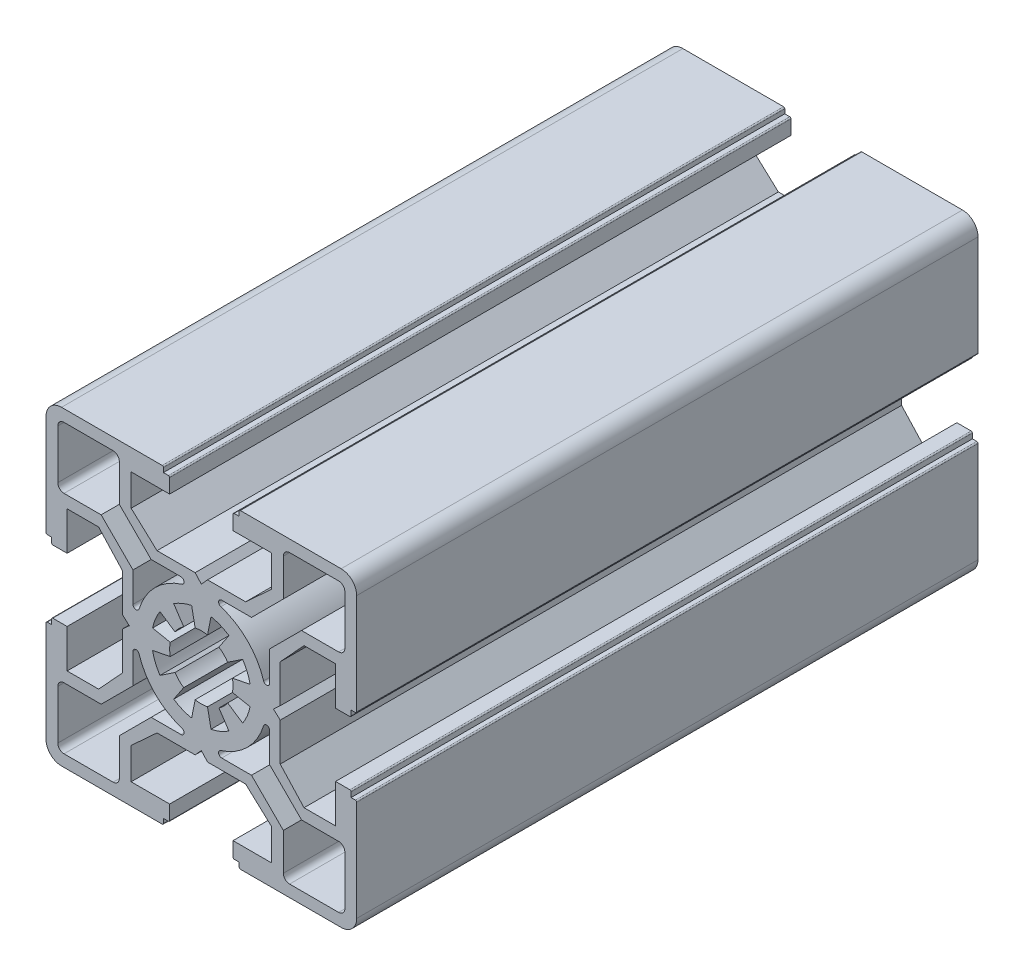
SolidWorks part; units mm, degrees
ref_plane "前视基准面" through (0, 0, 0) normal (0, 0, 1) x (1, 0, 0)
ref_plane "上视基准面" through (0, 0, 0) normal (0, 1, 0) x (1, 0, 0)
ref_plane "右视基准面" through (0, 0, 0) normal (1, 0, 0) x (0, 0, -1)
sketch "草图1" plane through (0, 0, 0) normal (0, 0, 1) x (1, 0, 0)
  line B0 (-6.3, 25) -> (-22.5, 25)
  line B1 (-25, 22.5) -> (-25, 6.3)
  line B2 (22.5, 25) -> (6.3, 25)
  line B3 (-25, -6.3) -> (-25, -22.5)
  line B4 (25, 6.3) -> (25, 22.5)
  line B5 (-22.5, -25) -> (-6.3, -25)
  line B6 (-6.1, -24.8) -> (-6.1, -24.1)
  line B7 (-6.1, -24.1) -> (-5.3, -24.1)
  line B8 (-5.1, -23.9) -> (-5.1, -21.6)
  line B9 (-5.1, -21.6) -> (-11.3, -21.6)
  line B10 (-11.3, -21.6) -> (-11.3, -16.53)
  line B11 (-11.3, -16.53) -> (-7.1302, -12.7)
  line B12 (-7.1302, -12.7) -> (-1, -12.7)
  line B13 (-1, -12.7) -> (0, -11.6)
  line B14 (0, -11.6) -> (1, -12.7)
  line B15 (1, -12.7) -> (7.1302, -12.7)
  line B16 (7.1302, -12.7) -> (11.3, -16.53)
  line B17 (11.3, -16.53) -> (11.3, -21.6)
  line B18 (11.3, -21.6) -> (5.1, -21.6)
  line B19 (5.1, -21.6) -> (5.1, -23.9)
  line B20 (5.3, -24.1) -> (6.1, -24.1)
  line B21 (6.1, -24.1) -> (6.1, -24.8)
  line B22 (25, -22.5) -> (25, -6.3)
  line B23 (6.3, -25) -> (22.5, -25)
  line B24 (2.8334, 4.2405) -> (4.4446, 6.6518)
  line B25 (1.5607, 7.8463) -> (0.995, 5.002)
  line B26 (-0.995, 5.002) -> (-1.5607, 7.8463)
  line B27 (-4.4446, 6.6518) -> (-2.8334, 4.2405)
  line B28 (-4.2405, 2.8334) -> (-6.6518, 4.4446)
  line B29 (-7.8463, 1.5607) -> (-5.002, 0.995)
  line B30 (-5.002, -0.995) -> (-7.8463, -1.5607)
  line B31 (-6.6518, -4.4446) -> (-4.2405, -2.8334)
  line B32 (-2.8334, -4.2405) -> (-4.4446, -6.6518)
  line B33 (-1.5607, -7.8463) -> (-0.995, -5.002)
  line B34 (0.995, -5.002) -> (1.5607, -7.8463)
  line B35 (4.4446, -6.6518) -> (2.8334, -4.2405)
  line B36 (4.2405, -2.8334) -> (6.6518, -4.4446)
  line B37 (7.8463, -1.5607) -> (5.002, -0.995)
  line B38 (5.002, 0.995) -> (7.8463, 1.5607)
  line B39 (6.6518, 4.4446) -> (4.2405, 2.8334)
  line B40 (3.2787, -11) -> (8.0757, -11)
  line B41 (8.0757, -11) -> (13.2, -16.1243)
  line B42 (13.2, -16.1243) -> (13.2, -22.1)
  line B43 (14.2, -23.1) -> (22.1, -23.1)
  line B44 (23.1, -22.1) -> (23.1, -14.2)
  line B45 (22.1, -13.2) -> (16.1243, -13.2)
  line B46 (16.1243, -13.2) -> (11, -8.0757)
  line B47 (11, -8.0757) -> (11, -3.2787)
  line B48 (-8.0757, 11) -> (-13.2, 16.1243)
  line B49 (-13.2, 16.1243) -> (-13.2, 22.1)
  line B50 (-14.2, 23.1) -> (-22.1, 23.1)
  line B51 (-23.1, 22.1) -> (-23.1, 14.2)
  line B52 (-22.1, 13.2) -> (-16.1243, 13.2)
  line B53 (-16.1243, 13.2) -> (-11, 8.0757)
  line B54 (-11, 8.0757) -> (-11, 3.2787)
  line B55 (-3.2787, 11) -> (-8.0757, 11)
  line B56 (13.2, 22.1) -> (13.2, 16.1243)
  line B57 (13.2, 16.1243) -> (8.0757, 11)
  line B58 (8.0757, 11) -> (3.2787, 11)
  line B59 (11, 3.2787) -> (11, 8.0757)
  line B60 (11, 8.0757) -> (16.1243, 13.2)
  line B61 (16.1243, 13.2) -> (22.1, 13.2)
  line B62 (23.1, 14.2) -> (23.1, 22.1)
  line B63 (22.1, 23.1) -> (14.2, 23.1)
  line B64 (-16.1243, -13.2) -> (-22.1, -13.2)
  line B65 (-23.1, -14.2) -> (-23.1, -22.1)
  line B66 (-22.1, -23.1) -> (-14.2, -23.1)
  line B67 (-13.2, -22.1) -> (-13.2, -16.1243)
  line B68 (-13.2, -16.1243) -> (-8.0757, -11)
  line B69 (-8.0757, -11) -> (-3.2787, -11)
  line B70 (-11, -3.2787) -> (-11, -8.0757)
  line B71 (-11, -8.0757) -> (-16.1243, -13.2)
  line B72 (24.8, -6.1) -> (24.1, -6.1)
  line B73 (24.1, -6.1) -> (24.1, -5.3)
  line B74 (23.9, -5.1) -> (21.6, -5.1)
  line B75 (21.6, -5.1) -> (21.6, -11.3)
  line B76 (21.6, -11.3) -> (16.53, -11.3)
  line B77 (16.53, -11.3) -> (12.7, -7.1302)
  line B78 (12.7, -7.1302) -> (12.7, -1)
  line B79 (12.7, -1) -> (11.6, 0)
  line B80 (11.6, 0) -> (12.7, 1)
  line B81 (12.7, 1) -> (12.7, 7.1302)
  line B82 (12.7, 7.1302) -> (16.53, 11.3)
  line B83 (16.53, 11.3) -> (21.6, 11.3)
  line B84 (21.6, 11.3) -> (21.6, 5.1)
  line B85 (21.6, 5.1) -> (23.9, 5.1)
  line B86 (24.1, 5.3) -> (24.1, 6.1)
  line B87 (24.1, 6.1) -> (24.8, 6.1)
  line B88 (6.1, 24.8) -> (6.1, 24.1)
  line B89 (6.1, 24.1) -> (5.3, 24.1)
  line B90 (5.1, 23.9) -> (5.1, 21.6)
  line B91 (5.1, 21.6) -> (11.3, 21.6)
  line B92 (11.3, 21.6) -> (11.3, 16.53)
  line B93 (11.3, 16.53) -> (7.1302, 12.7)
  line B94 (7.1302, 12.7) -> (1, 12.7)
  line B95 (1, 12.7) -> (0, 11.6)
  line B96 (0, 11.6) -> (-1, 12.7)
  line B97 (-1, 12.7) -> (-7.1302, 12.7)
  line B98 (-7.1302, 12.7) -> (-11.3, 16.53)
  line B99 (-11.3, 16.53) -> (-11.3, 21.6)
  line B100 (-11.3, 21.6) -> (-5.1, 21.6)
  line B101 (-5.1, 21.6) -> (-5.1, 23.9)
  line B102 (-5.3, 24.1) -> (-6.1, 24.1)
  line B103 (-6.1, 24.1) -> (-6.1, 24.8)
  line B104 (-24.8, 6.1) -> (-24.1, 6.1)
  line B105 (-24.1, 6.1) -> (-24.1, 5.3)
  line B106 (-23.9, 5.1) -> (-21.6, 5.1)
  line B107 (-21.6, 5.1) -> (-21.6, 11.3)
  line B108 (-21.6, 11.3) -> (-16.53, 11.3)
  line B109 (-16.53, 11.3) -> (-12.7, 7.1302)
  line B110 (-12.7, 7.1302) -> (-12.7, 1)
  line B111 (-12.7, 1) -> (-11.6, 0)
  line B112 (-11.6, 0) -> (-12.7, -1)
  line B113 (-12.7, -1) -> (-12.7, -7.1302)
  line B114 (-12.7, -7.1302) -> (-16.53, -11.3)
  line B115 (-16.53, -11.3) -> (-21.6, -11.3)
  line B116 (-21.6, -11.3) -> (-21.6, -5.1)
  line B117 (-21.6, -5.1) -> (-23.9, -5.1)
  line B118 (-24.1, -5.3) -> (-24.1, -6.1)
  line B119 (-24.1, -6.1) -> (-24.8, -6.1)
  arc B120 (-22.5, 25) -> (-25, 22.5) centre (-22.5, 22.5) ccw
  arc B121 (25, 22.5) -> (22.5, 25) centre (22.5, 22.5) ccw
  arc B122 (-25, -22.5) -> (-22.5, -25) centre (-22.5, -22.5) ccw
  arc B123 (-6.3, -25) -> (-6.1, -24.8) centre (-6.3, -24.8) ccw
  arc B124 (-5.3, -24.1) -> (-5.1, -23.9) centre (-5.3, -23.9) ccw
  arc B125 (5.1, -23.9) -> (5.3, -24.1) centre (5.3, -23.9) ccw
  arc B126 (6.1, -24.8) -> (6.3, -25) centre (6.3, -24.8) ccw
  arc B127 (22.5, -25) -> (25, -22.5) centre (22.5, -22.5) ccw
  arc B128 (4.2405, 2.8334) -> (2.8334, 4.2405) centre (0, 0) ccw
  arc B129 (4.4446, 6.6518) -> (1.5607, 7.8463) centre (0, 0) ccw
  arc B130 (0.995, 5.002) -> (-0.995, 5.002) centre (0, 0) ccw
  arc B131 (-1.5607, 7.8463) -> (-4.4446, 6.6518) centre (0, 0) ccw
  arc B132 (-2.8334, 4.2405) -> (-4.2405, 2.8334) centre (0, 0) ccw
  arc B133 (-6.6518, 4.4446) -> (-7.8463, 1.5607) centre (0, 0) ccw
  arc B134 (-5.002, 0.995) -> (-5.002, -0.995) centre (0, 0) ccw
  arc B135 (-7.8463, -1.5607) -> (-6.6518, -4.4446) centre (0, 0) ccw
  arc B136 (-4.2405, -2.8334) -> (-2.8334, -4.2405) centre (0, 0) ccw
  arc B137 (-4.4446, -6.6518) -> (-1.5607, -7.8463) centre (0, 0) ccw
  arc B138 (-0.995, -5.002) -> (0.995, -5.002) centre (0, 0) ccw
  arc B139 (1.5607, -7.8463) -> (4.4446, -6.6518) centre (0, 0) ccw
  arc B140 (2.8334, -4.2405) -> (4.2405, -2.8334) centre (0, 0) ccw
  arc B141 (6.6518, -4.4446) -> (7.8463, -1.5607) centre (0, 0) ccw
  arc B142 (5.002, -0.995) -> (5.002, 0.995) centre (0, 0) ccw
  arc B143 (7.8463, 1.5607) -> (6.6518, 4.4446) centre (0, 0) ccw
  arc B144 (3.1297, -10.0227) -> (10.0227, -3.1297) centre (0, 0) ccw
  arc B145 (3.1297, -10.0227) -> (3.2787, -11) centre (3.2787, -10.5) ccw
  arc B146 (13.2, -22.1) -> (14.2, -23.1) centre (14.2, -22.1) ccw
  arc B147 (22.1, -23.1) -> (23.1, -22.1) centre (22.1, -22.1) ccw
  arc B148 (23.1, -14.2) -> (22.1, -13.2) centre (22.1, -14.2) ccw
  arc B149 (11, -3.2787) -> (10.0227, -3.1297) centre (10.5, -3.2787) ccw
  arc B150 (-13.2, 22.1) -> (-14.2, 23.1) centre (-14.2, 22.1) ccw
  arc B151 (-22.1, 23.1) -> (-23.1, 22.1) centre (-22.1, 22.1) ccw
  arc B152 (-23.1, 14.2) -> (-22.1, 13.2) centre (-22.1, 14.2) ccw
  arc B153 (-11, 3.2787) -> (-10.0227, 3.1297) centre (-10.5, 3.2787) ccw
  arc B154 (-3.1297, 10.0227) -> (-10.0227, 3.1297) centre (0, 0) ccw
  arc B155 (-3.1297, 10.0227) -> (-3.2787, 11) centre (-3.2787, 10.5) ccw
  arc B156 (14.2, 23.1) -> (13.2, 22.1) centre (14.2, 22.1) ccw
  arc B157 (3.2787, 11) -> (3.1297, 10.0227) centre (3.2787, 10.5) ccw
  arc B158 (10.0227, 3.1297) -> (3.1297, 10.0227) centre (0, 0) ccw
  arc B159 (10.0227, 3.1297) -> (11, 3.2787) centre (10.5, 3.2787) ccw
  arc B160 (22.1, 13.2) -> (23.1, 14.2) centre (22.1, 14.2) ccw
  arc B161 (23.1, 22.1) -> (22.1, 23.1) centre (22.1, 22.1) ccw
  arc B162 (-22.1, -13.2) -> (-23.1, -14.2) centre (-22.1, -14.2) ccw
  arc B163 (-23.1, -22.1) -> (-22.1, -23.1) centre (-22.1, -22.1) ccw
  arc B164 (-14.2, -23.1) -> (-13.2, -22.1) centre (-14.2, -22.1) ccw
  arc B165 (-3.2787, -11) -> (-3.1297, -10.0227) centre (-3.2787, -10.5) ccw
  arc B166 (-10.0227, -3.1297) -> (-3.1297, -10.0227) centre (0, 0) ccw
  arc B167 (-10.0227, -3.1297) -> (-11, -3.2787) centre (-10.5, -3.2787) ccw
  arc B168 (25, -6.3) -> (24.8, -6.1) centre (24.8, -6.3) ccw
  arc B169 (24.1, -5.3) -> (23.9, -5.1) centre (23.9, -5.3) ccw
  arc B170 (23.9, 5.1) -> (24.1, 5.3) centre (23.9, 5.3) ccw
  arc B171 (24.8, 6.1) -> (25, 6.3) centre (24.8, 6.3) ccw
  arc B172 (6.3, 25) -> (6.1, 24.8) centre (6.3, 24.8) ccw
  arc B173 (5.3, 24.1) -> (5.1, 23.9) centre (5.3, 23.9) ccw
  arc B174 (-5.1, 23.9) -> (-5.3, 24.1) centre (-5.3, 23.9) ccw
  arc B175 (-6.1, 24.8) -> (-6.3, 25) centre (-6.3, 24.8) ccw
  arc B176 (-25, 6.3) -> (-24.8, 6.1) centre (-24.8, 6.3) ccw
  arc B177 (-24.1, 5.3) -> (-23.9, 5.1) centre (-23.9, 5.3) ccw
  arc B178 (-23.9, -5.1) -> (-24.1, -5.3) centre (-23.9, -5.3) ccw
  arc B179 (-24.8, -6.1) -> (-25, -6.3) centre (-24.8, -6.3) ccw
sketch_block_instance "A$C51142488-1"
sketch_block "A$C51142488"
extrude "凸台-拉伸1" add sketch "草图1" along normal blind 100
